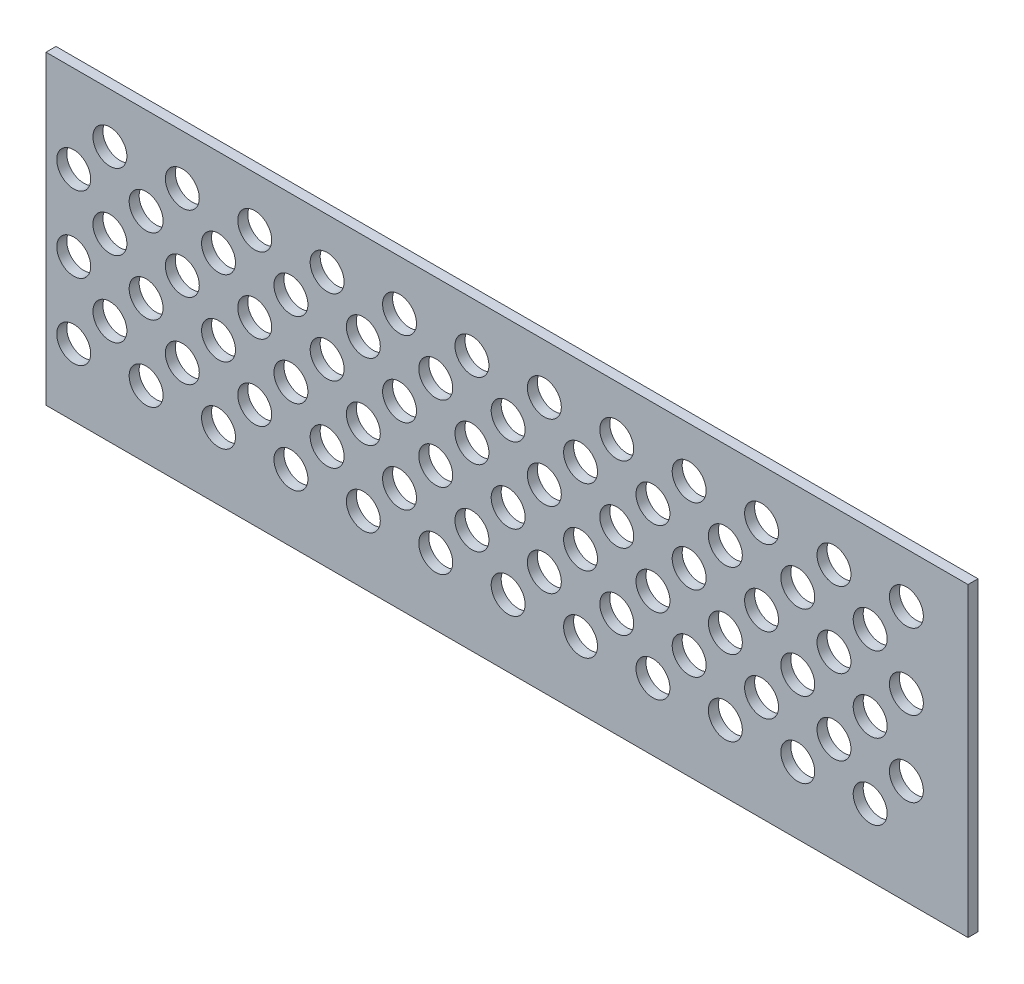
SolidWorks part; units mm, degrees
material "ABS"
ref_plane "X-Y Datum" through (0, 0, 0) normal (0, 0, 1) x (1, 0, 0)
ref_plane "X-Z Datum" through (0, 0, 0) normal (0, 1, 0) x (1, 0, 0)
ref_plane "Y-Z Datum" through (0, 0, 0) normal (1, 0, 0) x (0, 0, -1)
sketch "Sketch1" plane through (0, 0, 0) normal (0, 0, 1) x (1, 0, 0)
  line L1 (-286.05, 70.775) -> (286.05, 70.775)
  line L2 (-286.05, 70.775) -> (-286.05, -70.775)
  line L3 (-286.05, -70.775) -> (286.05, -70.775)
  line L4 (286.05, 70.775) -> (286.05, -70.775)
  line L5 (-286.05, 70.775) -> (286.05, -70.775) construction
  line L6 (-286.05, -70.775) -> (286.05, 70.775) construction
  line L13 (-292.875, -102.6) -> (292.875, -102.6)
  line L14 (-292.875, 91.65) -> (292.875, 91.65)
  line L15 (-292.875, 91.65) -> (-292.875, -102.6)
  line L16 (292.875, 91.65) -> (292.875, -102.6)
  line L17 (292.875, 70.775) -> (292.875, -70.775) construction
  line L18 (-286.05, 91.65) -> (286.05, 91.65) construction
  line L19 (-286.05, -102.6) -> (286.05, -102.6) construction
  line L20 (-292.875, 70.775) -> (-292.875, -70.775) construction
  line L21 (-275.275, -60) -> (-229.275, -60) construction
  circle A0 centre (-275.275, -60) radius 10.775
  circle A1 centre (-229.275, -60) radius 10.775 construction
  circle A2 centre (-252.275, -36) radius 10.775
  point P0 (0, 0)
  point P16 (-252.275, -60)
  dimension "D1" = 21.55
  dimension "D2" = 23
  dimension "D3" = 24
  dimension "D5" = 141.55
  dimension "D6" = 572.1
  dimension "D7" = 31.825
  dimension "D8" = 20.875
  dimension "D9" = 6.825
  dimension "D10" = 6.825
extrude "Boss-Extrude1" add sketch "Sketch1" along normal blind 6.35
sketch "Sketch3" plane through (0, 0, 6.35) normal (0, 0, 1) x (1, 0, 0)
  line L4 (286.05, 70.775) -> (-286.05, 70.775)
  line L5 (286.05, -70.775) -> (286.05, 70.775)
  line L6 (-286.05, -70.775) -> (286.05, -70.775)
  line L7 (-286.05, 70.775) -> (-286.05, -70.775)
  line L8 (286.05, 70.775) -> (-286.05, 70.775)
  line L9 (286.05, -70.775) -> (286.05, 70.775)
  line L10 (-286.05, -70.775) -> (286.05, -70.775)
  line L11 (-286.05, 70.775) -> (-286.05, -70.775)
  circle A1 centre (-252.275, -36) radius 10.775
  circle A2 centre (-252.275, -36) radius 10.775
  circle A3 centre (-275.275, -60) radius 10.775
  circle A4 centre (-275.275, -60) radius 10.775
  dimension "D1" = 0
  dimension "D2" = 0
  dimension "D3" = 0
extrude "Cut-Extrude1" cut sketch "Sketch3" against normal through all contours A4
sketch "Sketch4" plane through (0, 0, 6.35) normal (0, 0, 1) x (1, 0, 0)
  line L4 (286.05, 70.775) -> (-286.05, 70.775)
  line L5 (286.05, -70.775) -> (286.05, 70.775)
  line L6 (-286.05, -70.775) -> (286.05, -70.775)
  line L7 (-286.05, 70.775) -> (-286.05, -70.775)
  line L8 (286.05, 70.775) -> (-286.05, 70.775)
  line L9 (286.05, -70.775) -> (286.05, 70.775)
  line L10 (-286.05, -70.775) -> (286.05, -70.775)
  line L11 (-286.05, 70.775) -> (-286.05, -70.775)
  circle A1 centre (-252.275, -36) radius 10.775
  circle A2 centre (-252.275, -36) radius 10.775
  circle A3 centre (-275.275, -60) radius 10.775
  circle A4 centre (-275.275, -60) radius 10.775
  dimension "D1" = 0
  dimension "D2" = 0
  dimension "D3" = 0
extrude "Cut-Extrude2" cut sketch "Sketch4" against normal through all contours A2
pattern_linear "LPattern1" count 12 spacing 46 along (1, 0, 0) of "Cut-Extrude1", "Cut-Extrude2"
pattern_linear "LPattern2" count 3 spacing 48 along (0, 1, 0) of "LPattern1", "Cut-Extrude1", "Cut-Extrude2"
